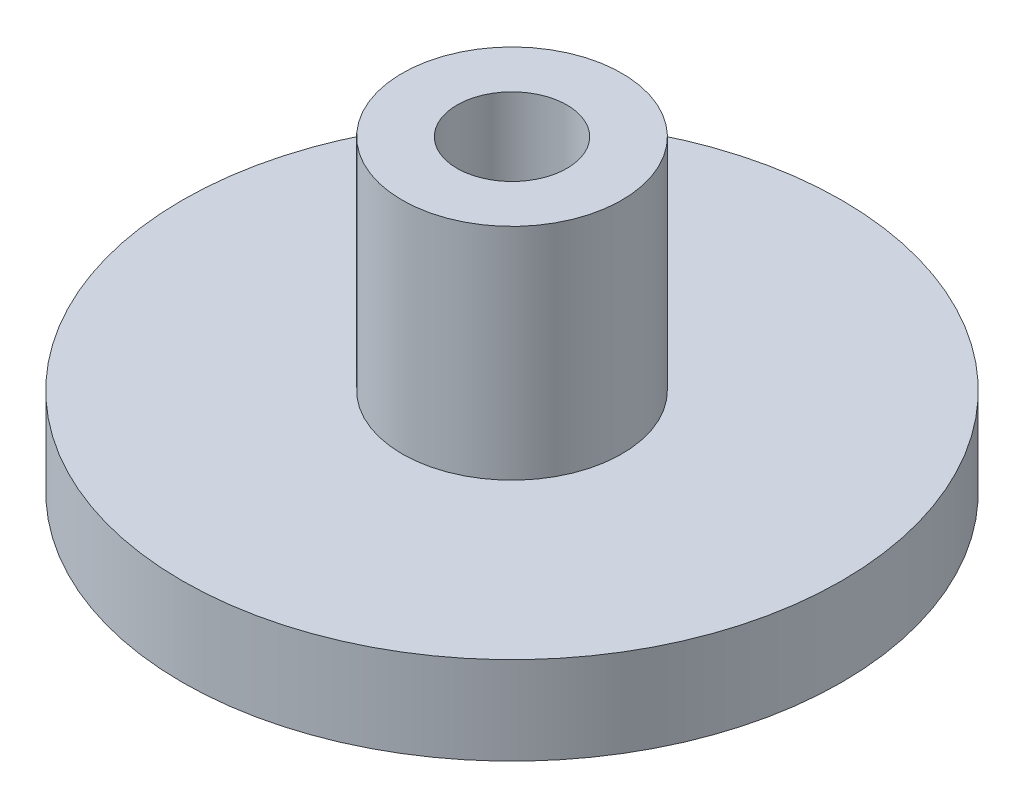
SolidWorks part; units mm, degrees
ref_plane "Front" through (0, 0, 0) normal (0, 0, 1) x (1, 0, 0)
ref_plane "Top" through (0, 0, 0) normal (0, 1, 0) x (1, 0, 0)
ref_plane "Right" through (0, 0, 0) normal (1, 0, 0) x (0, 0, -1)
sketch "Sketch1" plane through (0, 0, 0) normal (0, 1, 0) x (1, 0, 0)
  circle A0 centre (0, 0) radius 15
  circle A1 centre (0, 0) radius 2.5
  dimension "D1" = 5
  dimension "D2" = 30
extrude "Boss-Extrude1" add sketch "Sketch1" along normal blind 4
sketch "Sketch2" plane through (0, 4, 0) normal (0, 1, 0) x (1, 0, 0)
  circle A0 centre (0, 0) radius 5
  circle A1 centre (0, 0) radius 2.5 construction
  circle A2 centre (0, 0) radius 2.5
  dimension "D1" = 10
extrude "Boss-Extrude2" add sketch "Sketch2" along normal blind 10
